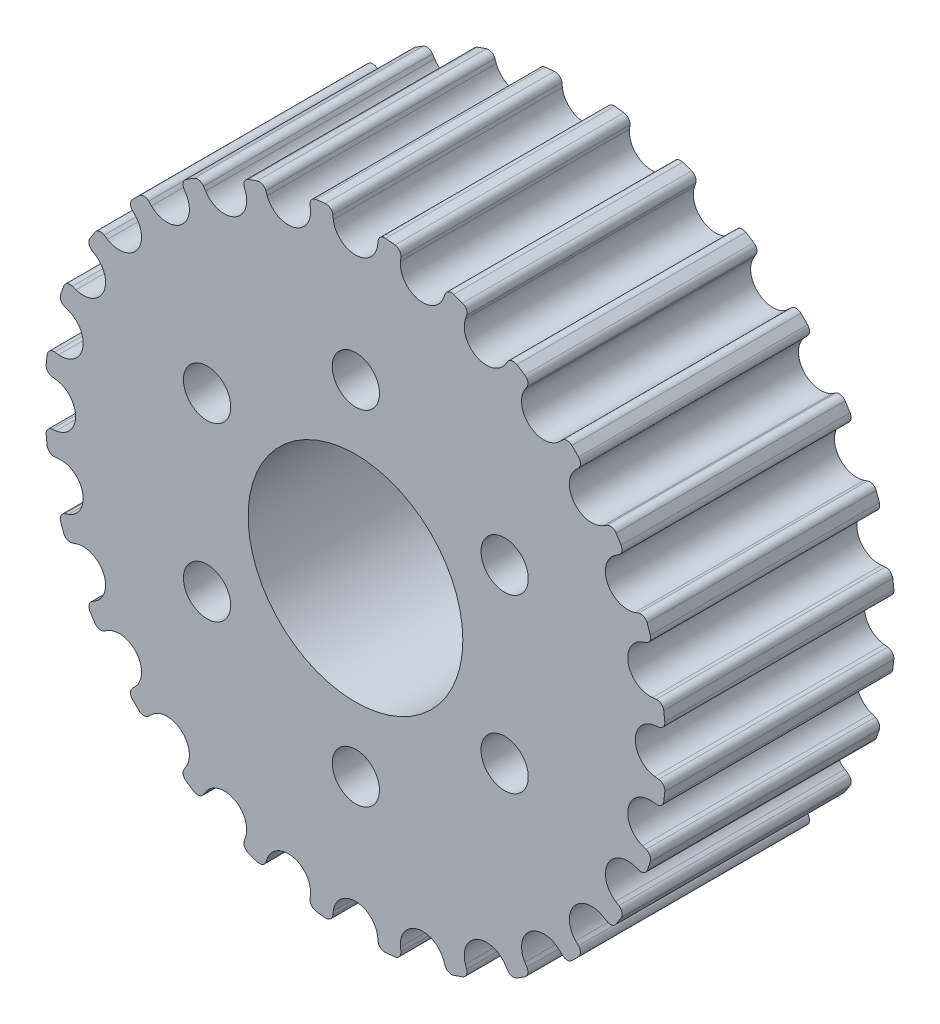
SolidWorks part; units mm, degrees
material "6061 合金"
ref_plane "前视基准面" through (0, 0, 0) normal (0, 0, 1) x (1, 0, 0)
ref_plane "上视基准面" through (0, 0, 0) normal (0, 1, 0) x (1, 0, 0)
ref_plane "右视基准面" through (0, 0, 0) normal (1, 0, 0) x (0, 0, -1)
sketch "草图1" plane through (0, 0, 0) normal (0, 0, 1) x (1, 0, 0)
  line L36 (1.554, 21.1844) -> (1.521, 20.9158)
  line L37 (-1.5757, 20.9158) -> (-1.6087, 21.1844)
  line L38 (-3.2001, 21.0051) -> (-3.1724, 20.7359)
  line L39 (-6.1915, 20.0468) -> (-6.2835, 20.3013)
  line L40 (-7.7951, 19.7724) -> (-7.7082, 19.5161)
  line L41 (-10.4983, 18.1724) -> (-10.6446, 18.4002)
  line L42 (-12.0006, 17.5481) -> (-11.8588, 17.3175)
  line L43 (-14.28, 15.3868) -> (-14.4733, 15.5762)
  line L44 (-15.6057, 14.4438) -> (-15.4162, 14.2505)
  line L45 (-17.347, 11.8294) -> (-17.5776, 11.9711)
  line L46 (-18.4296, 10.6151) -> (-18.2019, 10.4689)
  line L47 (-19.5455, 7.6788) -> (-19.8018, 7.7656)
  line L48 (-20.3308, 6.254) -> (-20.0762, 6.1621)
  line L49 (-20.7653, 3.143) -> (-21.0345, 3.1706)
  line L50 (-21.2138, 1.5792) -> (-20.9452, 1.5463)
  line L51 (-20.9452, -1.5505) -> (-21.2138, -1.5835)
  line L52 (-21.0345, -3.1748) -> (-20.7653, -3.1472)
  line L53 (-20.0762, -6.1663) -> (-20.3308, -6.2583)
  line L54 (-19.8018, -7.7698) -> (-19.5455, -7.683)
  line L55 (-18.2019, -10.4731) -> (-18.4296, -10.6194)
  line L56 (-17.5776, -11.9753) -> (-17.347, -11.8336)
  line L57 (-15.4162, -14.2548) -> (-15.6057, -14.448)
  line L58 (-14.4733, -15.5804) -> (-14.28, -15.391)
  line L59 (-11.8588, -17.3218) -> (-12.0006, -17.5524)
  line L60 (-10.6446, -18.4044) -> (-10.4983, -18.1767)
  line L61 (-7.7082, -19.5203) -> (-7.7951, -19.7766)
  line L62 (-6.2835, -20.3056) -> (-6.1915, -20.051)
  line L63 (-3.1724, -20.7401) -> (-3.2001, -21.0093)
  line L64 (-1.6087, -21.1886) -> (-1.5757, -20.92)
  line L65 (1.521, -20.92) -> (1.554, -21.1886)
  line L66 (3.1454, -21.0093) -> (3.1178, -20.7401)
  line L67 (6.1369, -20.051) -> (6.2288, -20.3056)
  line L68 (7.7404, -19.7766) -> (7.6536, -19.5203)
  line L69 (10.4436, -18.1767) -> (10.5899, -18.4044)
  line L70 (11.9459, -17.5524) -> (11.8042, -17.3218)
  line L71 (14.2253, -15.391) -> (14.4186, -15.5804)
  line L72 (15.551, -14.448) -> (15.3615, -14.2548)
  line L73 (17.2923, -11.8336) -> (17.5229, -11.9753)
  line L74 (18.375, -10.6194) -> (18.1472, -10.4731)
  line L75 (19.4909, -7.683) -> (19.7472, -7.7698)
  line L76 (20.2761, -6.2583) -> (20.0216, -6.1663)
  line L77 (20.7107, -3.1472) -> (20.9799, -3.1748)
  line L78 (21.1592, -1.5835) -> (20.8906, -1.5505)
  line L79 (20.8906, 1.5463) -> (21.1592, 1.5792)
  line L80 (20.9799, 3.1706) -> (20.7107, 3.143)
  line L81 (20.0216, 6.1621) -> (20.2761, 6.254)
  line L82 (19.7472, 7.7656) -> (19.4909, 7.6788)
  line L83 (18.1472, 10.4689) -> (18.375, 10.6151)
  line L84 (17.5229, 11.9711) -> (17.2923, 11.8294)
  line L85 (15.3615, 14.2505) -> (15.551, 14.4438)
  line L86 (14.4186, 15.5762) -> (14.2253, 15.3868)
  line L87 (11.8042, 17.3175) -> (11.9459, 17.5481)
  line L88 (10.5899, 18.4002) -> (10.4436, 18.1724)
  line L89 (7.6536, 19.5161) -> (7.7404, 19.7724)
  line L90 (6.2288, 20.3013) -> (6.1369, 20.0468)
  line L91 (3.1178, 20.7359) -> (3.1454, 21.0051)
  circle A72 centre (0, 0) radius 12 construction
  arc A73 (3.1454, 21.0051) -> (2.7289, 21.5302) centre (2.6679, 21.0541) ccw
  arc A74 (2.7289, 21.5302) -> (2.077, 21.6037) centre (-0.0273, -0.0021) ccw
  arc A75 (2.077, 21.6037) -> (1.554, 21.1844) centre (2.0305, 21.1259) ccw
  arc A76 (-1.5757, 20.9158) -> (1.521, 20.9158) centre (-0.0273, 21.1059) ccw
  arc A77 (-1.6087, 21.1844) -> (-2.1316, 21.6037) centre (-2.0851, 21.1259) ccw
  arc A78 (-2.1316, 21.6037) -> (-2.7835, 21.5302) centre (-0.0273, -0.0021) ccw
  arc A79 (-2.7835, 21.5302) -> (-3.2001, 21.0051) centre (-2.7226, 21.0541) ccw
  arc A80 (-6.1915, 20.0468) -> (-3.1724, 20.7359) centre (-4.7243, 20.5767) ccw
  arc A81 (-6.2835, 20.3013) -> (-6.8866, 20.5937) centre (-6.7349, 20.1383) ccw
  arc A82 (-6.8866, 20.5937) -> (-7.5058, 20.377) centre (-0.0273, -0.0021) ccw
  arc A83 (-7.5058, 20.377) -> (-7.7951, 19.7724) centre (-7.3404, 19.9264) ccw
  arc A84 (-10.4983, 18.1724) -> (-7.7082, 19.5161) centre (-9.1857, 19.0155) ccw
  arc A85 (-10.6446, 18.4002) -> (-11.2976, 18.551) centre (-11.0484, 18.1407) ccw
  arc A86 (-11.2976, 18.551) -> (-11.8531, 18.202) centre (-0.0273, -0.0021) ccw
  arc A87 (-11.8531, 18.202) -> (-12.0006, 17.5481) centre (-11.5916, 17.7994) ccw
  arc A88 (-14.28, 15.3868) -> (-11.8588, 17.3175) centre (-13.1879, 16.5008) ccw
  arc A89 (-14.4733, 15.5762) -> (-15.1435, 15.5779) centre (-14.8093, 15.2334) ccw
  arc A90 (-15.1435, 15.5779) -> (-15.6074, 15.1141) centre (-0.0273, -0.0021) ccw
  arc A91 (-15.6074, 15.1141) -> (-15.6057, 14.4438) centre (-15.2629, 14.7798) ccw
  arc A92 (-17.347, 11.8294) -> (-15.4162, 14.2505) centre (-16.5302, 13.1585) ccw
  arc A93 (-17.5776, 11.9711) -> (-18.2314, 11.8236) centre (-17.8289, 11.5622) ccw
  arc A94 (-18.2314, 11.8236) -> (-18.5804, 11.2682) centre (-0.0273, -0.0021) ccw
  arc A95 (-18.5804, 11.2682) -> (-18.4296, 10.6151) centre (-18.1702, 11.019) ccw
  arc A96 (-19.5455, 7.6788) -> (-18.2019, 10.4689) centre (-19.045, 9.1563) ccw
  arc A97 (-19.8018, 7.7656) -> (-20.4065, 7.4764) centre (-19.9559, 7.311) ccw
  arc A98 (-20.4065, 7.4764) -> (-20.6231, 6.8572) centre (-0.0273, -0.0021) ccw
  arc A99 (-20.6231, 6.8572) -> (-20.3308, 6.254) centre (-20.1677, 6.7055) ccw
  arc A100 (-20.7653, 3.143) -> (-20.0762, 6.1621) centre (-20.6061, 4.6949) ccw
  arc A101 (-21.0345, 3.1706) -> (-21.5596, 2.7541) centre (-21.0835, 2.6931) ccw
  arc A102 (-21.5596, 2.7541) -> (-21.6331, 2.1022) centre (-0.0273, -0.0021) ccw
  arc A103 (-21.6331, 2.1022) -> (-21.2138, 1.5792) centre (-21.1554, 2.0557) ccw
  arc A104 (-20.9452, -1.5505) -> (-20.9452, 1.5463) centre (-21.1353, -0.0021) ccw
  arc A105 (-21.2138, -1.5835) -> (-21.6331, -2.1064) centre (-21.1554, -2.0599) ccw
  arc A106 (-21.6331, -2.1064) -> (-21.5596, -2.7583) centre (-0.0273, -0.0021) ccw
  arc A107 (-21.5596, -2.7583) -> (-21.0345, -3.1748) centre (-21.0835, -2.6974) ccw
  arc A108 (-20.0762, -6.1663) -> (-20.7653, -3.1472) centre (-20.6061, -4.6991) ccw
  arc A109 (-20.3308, -6.2583) -> (-20.6231, -6.8614) centre (-20.1677, -6.7097) ccw
  arc A110 (-20.6231, -6.8614) -> (-20.4065, -7.4806) centre (-0.0273, -0.0021) ccw
  arc A111 (-20.4065, -7.4806) -> (-19.8018, -7.7698) centre (-19.9559, -7.3152) ccw
  arc A112 (-18.2019, -10.4731) -> (-19.5455, -7.683) centre (-19.045, -9.1605) ccw
  arc A113 (-18.4296, -10.6194) -> (-18.5804, -11.2724) centre (-18.1702, -11.0232) ccw
  arc A114 (-18.5804, -11.2724) -> (-18.2314, -11.8279) centre (-0.0273, -0.0021) ccw
  arc A115 (-18.2314, -11.8279) -> (-17.5776, -11.9753) centre (-17.8289, -11.5664) ccw
  arc A116 (-15.4162, -14.2548) -> (-17.347, -11.8336) centre (-16.5302, -13.1627) ccw
  arc A117 (-15.6057, -14.448) -> (-15.6074, -15.1183) centre (-15.2629, -14.7841) ccw
  arc A118 (-15.6074, -15.1183) -> (-15.1435, -15.5822) centre (-0.0273, -0.0021) ccw
  arc A119 (-15.1435, -15.5822) -> (-14.4733, -15.5804) centre (-14.8093, -15.2377) ccw
  arc A120 (-11.8588, -17.3218) -> (-14.28, -15.391) centre (-13.1879, -16.505) ccw
  arc A121 (-12.0006, -17.5524) -> (-11.8531, -18.2062) centre (-11.5916, -17.8037) ccw
  arc A122 (-11.8531, -18.2062) -> (-11.2976, -18.5552) centre (-0.0273, -0.0021) ccw
  arc A123 (-11.2976, -18.5552) -> (-10.6446, -18.4044) centre (-11.0484, -18.145) ccw
  arc A124 (-7.7082, -19.5203) -> (-10.4983, -18.1767) centre (-9.1857, -19.0198) ccw
  arc A125 (-7.7951, -19.7766) -> (-7.5058, -20.3813) centre (-7.3404, -19.9306) ccw
  arc A126 (-7.5058, -20.3813) -> (-6.8866, -20.5979) centre (-0.0273, -0.0021) ccw
  arc A127 (-6.8866, -20.5979) -> (-6.2835, -20.3056) centre (-6.7349, -20.1425) ccw
  arc A128 (-3.1724, -20.7401) -> (-6.1915, -20.051) centre (-4.7243, -20.5809) ccw
  arc A129 (-3.2001, -21.0093) -> (-2.7835, -21.5344) centre (-2.7226, -21.0583) ccw
  arc A130 (-2.7835, -21.5344) -> (-2.1316, -21.6079) centre (-0.0273, -0.0021) ccw
  arc A131 (-2.1316, -21.6079) -> (-1.6087, -21.1886) centre (-2.0851, -21.1301) ccw
  arc A132 (1.521, -20.92) -> (-1.5757, -20.92) centre (-0.0273, -21.1101) ccw
  arc A133 (1.554, -21.1886) -> (2.077, -21.6079) centre (2.0305, -21.1301) ccw
  arc A134 (2.077, -21.6079) -> (2.7289, -21.5344) centre (-0.0273, -0.0021) ccw
  arc A135 (2.7289, -21.5344) -> (3.1454, -21.0093) centre (2.6679, -21.0583) ccw
  arc A136 (6.1369, -20.051) -> (3.1178, -20.7401) centre (4.6696, -20.5809) ccw
  arc A137 (6.2288, -20.3056) -> (6.832, -20.5979) centre (6.6803, -20.1425) ccw
  arc A138 (6.832, -20.5979) -> (7.4512, -20.3813) centre (-0.0273, -0.0021) ccw
  arc A139 (7.4512, -20.3813) -> (7.7404, -19.7766) centre (7.2858, -19.9306) ccw
  arc A140 (10.4436, -18.1767) -> (7.6536, -19.5203) centre (9.1311, -19.0198) ccw
  arc A141 (10.5899, -18.4044) -> (11.243, -18.5552) centre (10.9938, -18.145) ccw
  arc A142 (11.243, -18.5552) -> (11.7984, -18.2062) centre (-0.0273, -0.0021) ccw
  arc A143 (11.7984, -18.2062) -> (11.9459, -17.5524) centre (11.5369, -17.8037) ccw
  arc A144 (14.2253, -15.391) -> (11.8042, -17.3218) centre (13.1333, -16.505) ccw
  arc A145 (14.4186, -15.5804) -> (15.0889, -15.5822) centre (14.7546, -15.2377) ccw
  arc A146 (15.0889, -15.5822) -> (15.5527, -15.1183) centre (-0.0273, -0.0021) ccw
  arc A147 (15.5527, -15.1183) -> (15.551, -14.448) centre (15.2082, -14.7841) ccw
  arc A148 (17.2923, -11.8336) -> (15.3615, -14.2548) centre (16.4756, -13.1627) ccw
  arc A149 (17.5229, -11.9753) -> (18.1768, -11.8279) centre (17.7742, -11.5664) ccw
  arc A150 (18.1768, -11.8279) -> (18.5258, -11.2724) centre (-0.0273, -0.0021) ccw
  arc A151 (18.5258, -11.2724) -> (18.375, -10.6194) centre (18.1155, -11.0232) ccw
  arc A152 (19.4909, -7.683) -> (18.1472, -10.4731) centre (18.9903, -9.1605) ccw
  arc A153 (19.7472, -7.7698) -> (20.3518, -7.4806) centre (19.9012, -7.3152) ccw
  arc A154 (20.3518, -7.4806) -> (20.5685, -6.8614) centre (-0.0273, -0.0021) ccw
  arc A155 (20.5685, -6.8614) -> (20.2761, -6.2583) centre (20.1131, -6.7097) ccw
  arc A156 (20.7107, -3.1472) -> (20.0216, -6.1663) centre (20.5515, -4.6991) ccw
  arc A157 (20.9799, -3.1748) -> (21.505, -2.7583) centre (21.0289, -2.6974) ccw
  arc A158 (21.505, -2.7583) -> (21.5784, -2.1064) centre (-0.0273, -0.0021) ccw
  arc A159 (21.5784, -2.1064) -> (21.1592, -1.5835) centre (21.1007, -2.0599) ccw
  arc A160 (20.8906, 1.5463) -> (20.8906, -1.5505) centre (21.0807, -0.0021) ccw
  arc A161 (21.1592, 1.5792) -> (21.5784, 2.1022) centre (21.1007, 2.0557) ccw
  arc A162 (21.5784, 2.1022) -> (21.505, 2.7541) centre (-0.0273, -0.0021) ccw
  arc A163 (21.505, 2.7541) -> (20.9799, 3.1706) centre (21.0289, 2.6931) ccw
  arc A164 (20.0216, 6.1621) -> (20.7107, 3.143) centre (20.5515, 4.6949) ccw
  arc A165 (20.2761, 6.254) -> (20.5685, 6.8572) centre (20.1131, 6.7055) ccw
  arc A166 (20.5685, 6.8572) -> (20.3518, 7.4764) centre (-0.0273, -0.0021) ccw
  arc A167 (20.3518, 7.4764) -> (19.7472, 7.7656) centre (19.9012, 7.311) ccw
  arc A168 (18.1472, 10.4689) -> (19.4909, 7.6788) centre (18.9903, 9.1563) ccw
  arc A169 (18.375, 10.6151) -> (18.5258, 11.2682) centre (18.1155, 11.019) ccw
  arc A170 (18.5258, 11.2682) -> (18.1768, 11.8236) centre (-0.0273, -0.0021) ccw
  arc A171 (18.1768, 11.8236) -> (17.5229, 11.9711) centre (17.7742, 11.5622) ccw
  arc A172 (15.3615, 14.2505) -> (17.2923, 11.8294) centre (16.4756, 13.1585) ccw
  arc A173 (15.551, 14.4438) -> (15.5527, 15.1141) centre (15.2082, 14.7798) ccw
  arc A174 (15.5527, 15.1141) -> (15.0889, 15.5779) centre (-0.0273, -0.0021) ccw
  arc A175 (15.0889, 15.5779) -> (14.4186, 15.5762) centre (14.7546, 15.2334) ccw
  arc A176 (11.8042, 17.3175) -> (14.2253, 15.3868) centre (13.1333, 16.5008) ccw
  arc A177 (11.9459, 17.5481) -> (11.7984, 18.202) centre (11.5369, 17.7994) ccw
  arc A178 (11.7984, 18.202) -> (11.243, 18.551) centre (-0.0273, -0.0021) ccw
  arc A179 (11.243, 18.551) -> (10.5899, 18.4002) centre (10.9938, 18.1407) ccw
  arc A180 (7.6536, 19.5161) -> (10.4436, 18.1724) centre (9.1311, 19.0155) ccw
  arc A181 (7.7404, 19.7724) -> (7.4512, 20.377) centre (7.2858, 19.9264) ccw
  arc A182 (7.4512, 20.377) -> (6.832, 20.5937) centre (-0.0273, -0.0021) ccw
  arc A183 (6.832, 20.5937) -> (6.2288, 20.3013) centre (6.6803, 20.1383) ccw
  arc A184 (3.1178, 20.7359) -> (6.1369, 20.0468) centre (4.6696, 20.5767) ccw
  circle A185 centre (-0.0273, -0.0021) radius 7.5
  dimension "D1" = 15
  dimension "D2" = 24
extrude "凸台-拉伸1" add sketch "草图1" along normal blind 16
sketch "草图7" plane through (0, 0, 0) normal (0, 0, -1) x (-1, 0, 0)
  circle A0 centre (0, 0) radius 12 construction
  circle A8 centre (0, 12) radius 1.65
  circle A9 centre (10.3923, 6) radius 1.65
  circle A10 centre (10.3923, -6) radius 1.65
  circle A11 centre (0, -12) radius 1.65
  circle A12 centre (-10.3923, -6) radius 1.65
  circle A13 centre (-10.3923, 6) radius 1.65
  point P3 (0, 12)
  point P6 (10.3923, 6)
  point P7 (10.3923, -6)
  point P8 (0, -12)
  point P9 (-10.3923, -6)
  point P10 (-10.3923, 6)
  point P11 (0, 0)
  point P24 (0, 0)
  point P26 (0, 0)
  dimension "D1" = 24
  dimension "D3" = 6
  dimension "D4" = 3.3
  dimension "D2" = 6
ref_plane "基准面1" through (0, 0, -10) normal (0, 0, -1) x (-1, 0, 0)
sketch "草图8" plane through (0, 0, -10) normal (0, 0, -1) x (-1, 0, 0)
  circle A0 centre (0, 0) radius 12 construction
ref_plane "基准面2" through (0, 0, 0) normal (0, 0, -1) x (-1, 0, 0)
sketch "草图9" plane through (0, 0, 0) normal (0, 0, -1) x (-1, 0, 0)
  circle A0 centre (0, 12) radius 1.65
  circle A1 centre (0, 0) radius 12 construction
  circle A2 centre (10.3923, 6) radius 1.65
  circle A3 centre (10.3923, -6) radius 1.65
  circle A4 centre (0, -12) radius 1.65
  circle A5 centre (-10.3923, -6) radius 1.65
  circle A6 centre (-10.3923, 6) radius 1.65
  point P16 (0, 0)
  dimension "D1" = 6
extrude "切除-拉伸2" cut sketch "草图9" against normal blind 16
